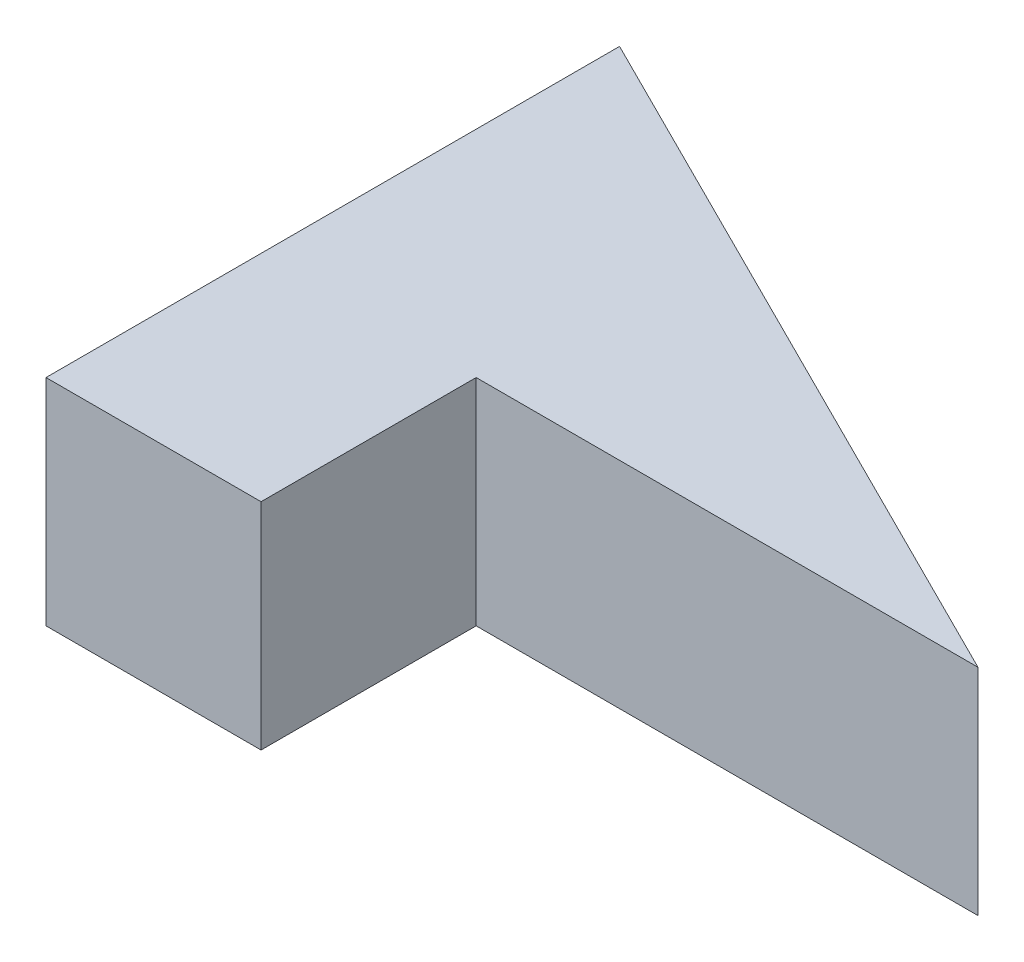
SolidWorks part; units mm, degrees
ref_plane "Front Plane" through (0, 0, 0) normal (0, 0, 1) x (1, 0, 0)
ref_plane "Top Plane" through (0, 0, 0) normal (0, 1, 0) x (1, 0, 0)
ref_plane "Right Plane" through (0, 0, 0) normal (1, 0, 0) x (0, 0, -1)
sketch "Sketch1" plane through (0, 0, 0) normal (0, 1, 0) x (1, 0, 0)
  line L0 (3, 0) -> (10, 0)
  line L1 (10, 0) -> (0, 5)
  line L2 (0, 5) -> (0, 0)
  line L3 (0, 0) -> (0, -3)
  line L4 (0, -3) -> (3, -3)
  line L5 (3, -3) -> (3, 0)
  dimension "D1" = 10
  dimension "D2" = 5
  dimension "D3" = 3
  dimension "D4" = 3
extrude "Boss-Extrude1" add sketch "Sketch1" along normal blind 3
